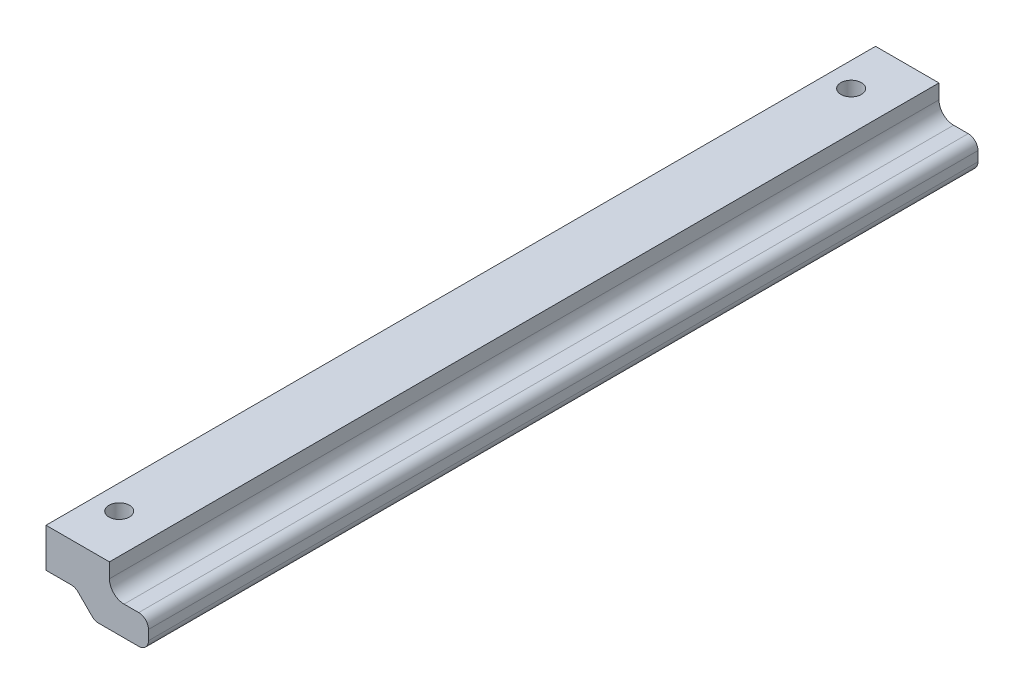
SolidWorks part; units mm, degrees
ref_plane "Front Plane" through (0, 0, 0) normal (0, 0, 1) x (1, 0, 0)
ref_plane "Top Plane" through (0, 0, 0) normal (0, 1, 0) x (1, 0, 0)
ref_plane "Right Plane" through (0, 0, 0) normal (1, 0, 0) x (0, 0, -1)
sketch "Sketch1" plane through (0, 0, 0) normal (0, 0, 1) x (1, 0, 0)
  line L1 (13, -6) -> (13, 0)
  line L2 (55, 0) -> (-55, 0) construction
  line L6 (13, -6) -> (21, -6)
  line L7 (21, -6) -> (21, -12)
  line L8 (0, 0) -> (13, 0)
  line L9 (21, -12) -> (10, -12)
  line L10 (10, -12) -> (6, -8)
  line L11 (6, -8) -> (0, -8)
  line L13 (0, -55) -> (0, 55) construction
  line L14 (0, -8) -> (0, 0)
  dimension "D1" = 6
  dimension "D2" = 6
  dimension "D3" = 8
  dimension "D4" = 10
  dimension "D5" = 8
  dimension "D6" = 45
extrude "Boss-Extrude1" add sketch "Sketch1" against normal blind 170
fillet "Fillet2" radius 3 1 edges at (13, -6, -85)
sketch "Sketch2" plane through (0, 0, 0) normal (0, 1, 0) x (1, 0, 0)
  line L0 (0, -6.6) -> (0, 6.6) construction
  line L1 (-6.6, 0) -> (6.6, 0) construction
  circle A0 centre (5, 10) radius 2.1
  circle A1 centre (5, 160) radius 2.1
  dimension "D3" = 4.2
  dimension "D1" = 5
  dimension "D2" = 10
  dimension "D4" = 150
extrude "Cut-Extrude1" cut sketch "Sketch2" against normal up to surface (8 mm away) up to face at (3, -8, -85)
sketch "Sketch3" plane through (0, 0, 0) normal (0, 1, 0) x (1, 0, 0)
  line L0 (0, -6.6) -> (0, 6.6) construction
  line L1 (1.55, 11.9919) -> (1.55, 8.0081)
  line L16 (1.55, 8.0081) -> (5, 6.0163)
  line L17 (5, 6.0163) -> (8.45, 8.0081)
  line L18 (8.45, 8.0081) -> (8.45, 11.9919)
  line L19 (8.45, 11.9919) -> (5, 13.9837)
  line L20 (5, 13.9837) -> (1.55, 11.9919)
  line L22 (1.55, 161.9919) -> (1.55, 158.0081)
  line L23 (1.55, 158.0081) -> (5, 156.0163)
  line L24 (5, 156.0163) -> (8.45, 158.0081)
  line L25 (8.45, 158.0081) -> (8.45, 161.9919)
  line L26 (8.45, 161.9919) -> (5, 163.9837)
  line L27 (5, 163.9837) -> (1.55, 161.9919)
  circle A2 centre (5, 10) radius 3.45 construction
  circle A3 centre (5, 160) radius 3.45 construction
  dimension "D1" = 6.9
  dimension "D2" = 6.9
extrude "Cut-Extrude2" cut sketch "Sketch3" along normal offset from surface (9 mm away) 3 from surface at -12 up to face at (5, 0, -7.9) starting at face at (15.5, -12, -85)
fillet "Fillet3" radius 2 2 edges at (21, -12, -85) (21, -6, -85)
sketch "Sketch4" plane through (0, 0, 0) normal (-1, 0, 0) x (0, 0, 1)
  line L0 (-170, 0) -> (0, 0) construction
  line L1 (-41.4426, 0) -> (-33.4426, 0)
  line L2 (-41.4426, 0) -> (-41.4426, -5)
  line L3 (-41.4426, -5) -> (-33.4426, -5)
  line L4 (-33.4426, 0) -> (-33.4426, -5)
  dimension "D1" = 5
  dimension "D2" = 8
extrude "Cut-Extrude3" [suppressed] cut sketch "Sketch4" against normal up to surface (21 mm away)
fillet "Fillet4" radius 2 4 edges at (6, -8, -166.7032) (6, -8, -85) (10, -12, -85) (6, -8, -3.2968)
